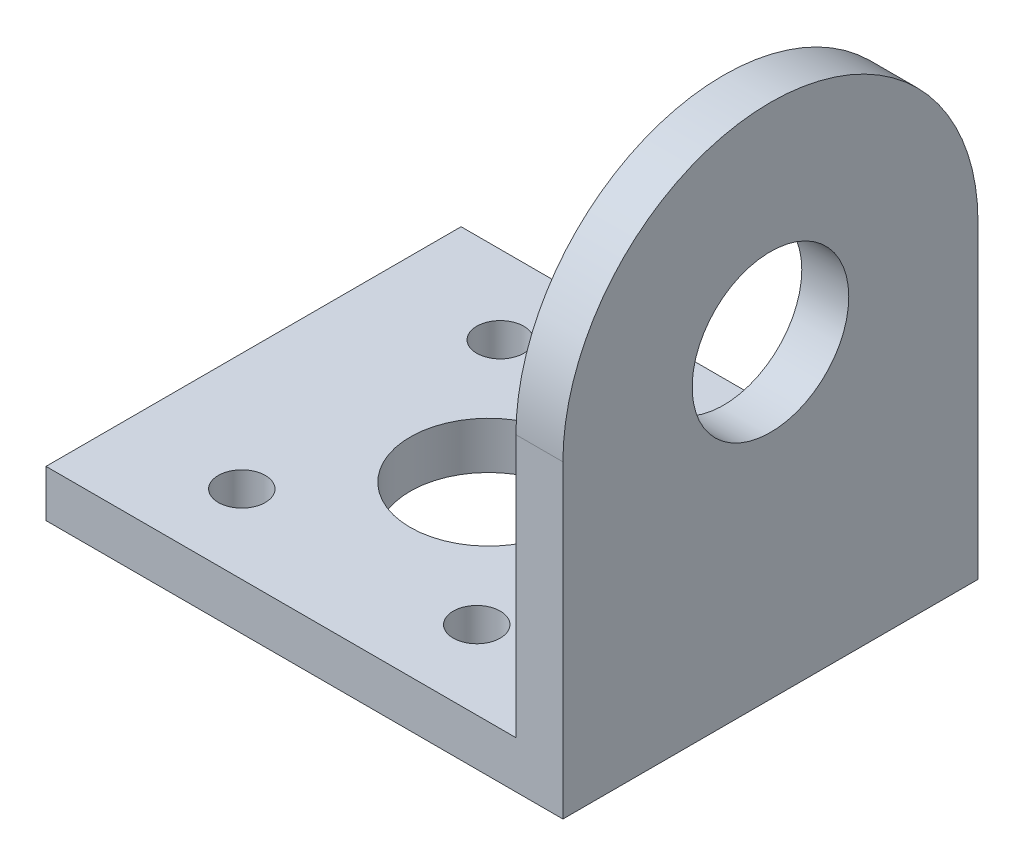
SolidWorks part; units mm, degrees
ref_plane "Front Plane" through (0, 0, 0) normal (0, 0, 1) x (1, 0, 0)
ref_plane "Top Plane" through (0, 0, 0) normal (0, 1, 0) x (1, 0, 0)
ref_plane "Right Plane" through (0, 0, 0) normal (1, 0, 0) x (0, 0, -1)
sketch "Sketch1" plane through (0, 0, 0) normal (0, 1, 0) x (1, 0, 0)
  line L0 (0, -14.5443) -> (0, 21.3613) construction
  line L1 (-15, 13.25) -> (15, 13.25)
  line L2 (-15, 13.25) -> (-15, -13.25)
  line L3 (-15, -13.25) -> (15, -13.25)
  line L4 (15, 13.25) -> (15, -13.25)
  line L5 (-15, 13.25) -> (15, -13.25) construction
  line L6 (-15, -13.25) -> (15, 13.25) construction
  line L7 (-19.6503, 0) -> (29.797, 0) construction
  circle A0 centre (0, 0) radius 5
  circle A1 centre (7.5, 8.25) radius 1.5
  circle A5 centre (-7.5, 8.25) radius 1.5
  circle A6 centre (-7.5, -8.25) radius 1.5
  circle A7 centre (7.5, -8.25) radius 1.5
  point P0 (0, 0)
  dimension "D1" = 10
  dimension "D4" = 7.5
  dimension "D6" = 3
  dimension "D5" = 5
  dimension "D2" = 26.5
  dimension "D3" = 30
extrude "Boss-Extrude1" add sketch "Sketch1" along normal blind 3
sketch "Sketch2" plane through (0, 0, 0) normal (0, 1, 0) x (1, 0, 0)
  line L0 (-15, -13.25) -> (15, -13.25) construction
  line L1 (15, 13.25) -> (18, 13.25)
  line L2 (15, 13.25) -> (15, -13.25)
  line L3 (15, -13.25) -> (18, -13.25)
  line L4 (18, 13.25) -> (18, -13.25)
  dimension "D1" = 3
  dimension "D2" = 0
extrude "Boss-Extrude2" add sketch "Sketch2" along normal blind 33
sketch "Sketch3" plane through (15, 0, 0) normal (-1, 0, 0) x (0, 0, 1)
  line L0 (-13.25, 33) -> (13.25, 33) construction
  line L2 (-13.25, 33) -> (-13.25, 19.75)
  line L4 (-13.25, 33) -> (13.25, 33)
  line L5 (13.25, 33) -> (13.25, 19.75)
  arc A0 (13.25, 19.75) -> (-13.25, 19.75) centre (0, 19.75) ccw
  line M2 (13.25, 3) -> (13.25, 33)
  line M3 (13.25, 33) -> (-13.25, 33)
  line M4 (-13.25, 33) -> (-13.25, 3)
  dimension "D1" = 26.5
extrude "Cut-Extrude1" cut sketch "Sketch3" against normal blind 33 contours A0 L4 M4 | A0 M2 M3
sketch "Sketch4" plane through (18, 0, 0) normal (1, 0, 0) x (0, 0, -1)
  circle A0 centre (0, 19.75) radius 5
  dimension "D1" = 10
extrude "Cut-Extrude2" cut sketch "Sketch4" against normal through all
